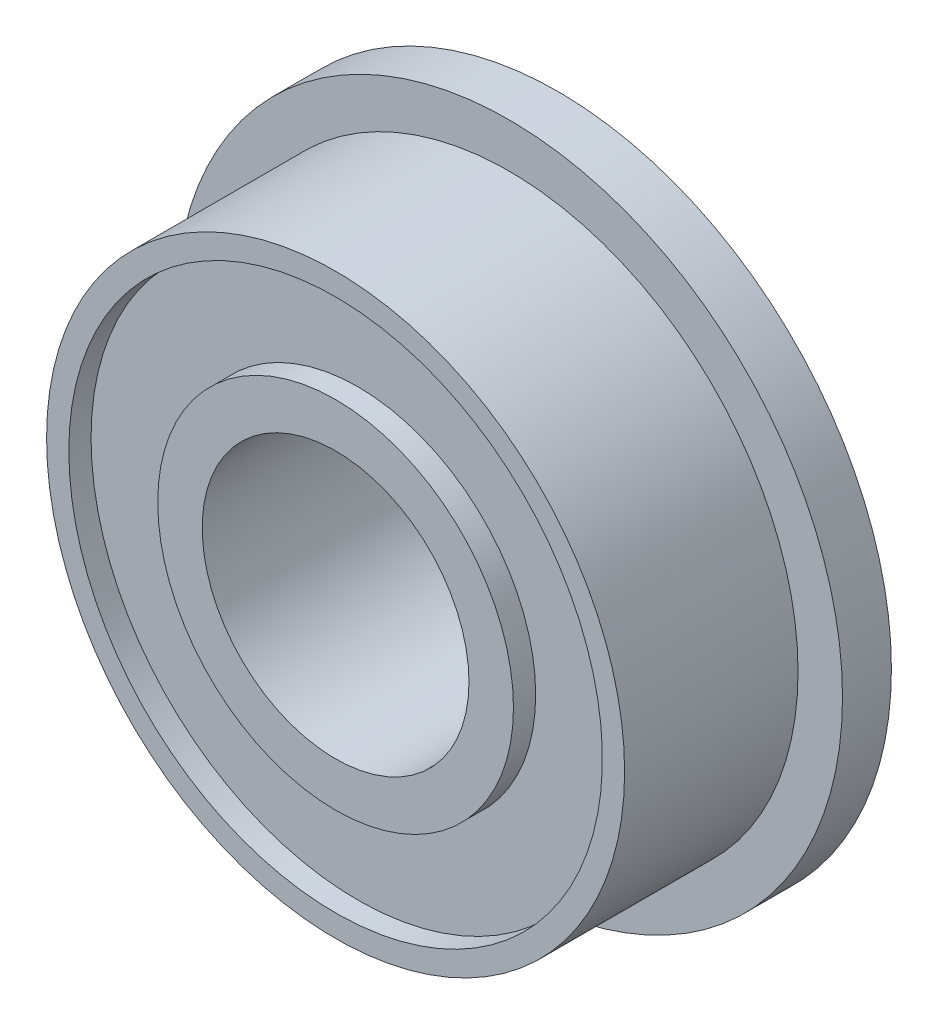
SolidWorks part; units mm, degrees
ref_plane "Front Plane" through (0, 0, 0) normal (0, 0, 1) x (1, 0, 0)
ref_plane "Top Plane" through (0, 0, 0) normal (0, 1, 0) x (1, 0, 0)
ref_plane "Right Plane" through (0, 0, 0) normal (1, 0, 0) x (0, 0, -1)
sketch "Sketch1" plane through (0, 0, 0) normal (0, 0, 1) x (1, 0, 0)
  circle A0 centre (0, 0) radius 7.5
  circle A1 centre (0, 0) radius 3
  dimension "D1" = 6
  dimension "D2" = 15
extrude "Boss-Extrude1" add sketch "Sketch1" along normal blind 1.1
sketch "Sketch2" plane through (0, 0, 1.1) normal (0, 0, 1) x (1, 0, 0)
  circle A0 centre (0, 0) radius 3
  circle A1 centre (0, 0) radius 3 construction
  circle A2 centre (0, 0) radius 6.5
  dimension "D1" = 13
extrude "Boss-Extrude2" add sketch "Sketch2" along normal blind 3.9
ref_plane "Plane1" through (0, 0, 2.5) normal (0, 0, 1) x (1, 0, 0)
sketch "Sketch3" plane through (0, 0, 0) normal (0, 0, -1) x (-1, 0, 0)
  circle A0 centre (0, 0) radius 4
  circle A1 centre (0, 0) radius 6
  dimension "D1" = 8
  dimension "D2" = 12
extrude "Cut-Extrude1" cut sketch "Sketch3" against normal blind 0.5
mirror "Mirror1" about plane through (0, 0, 2.5) normal (0, 0, 1) of "Cut-Extrude1"
